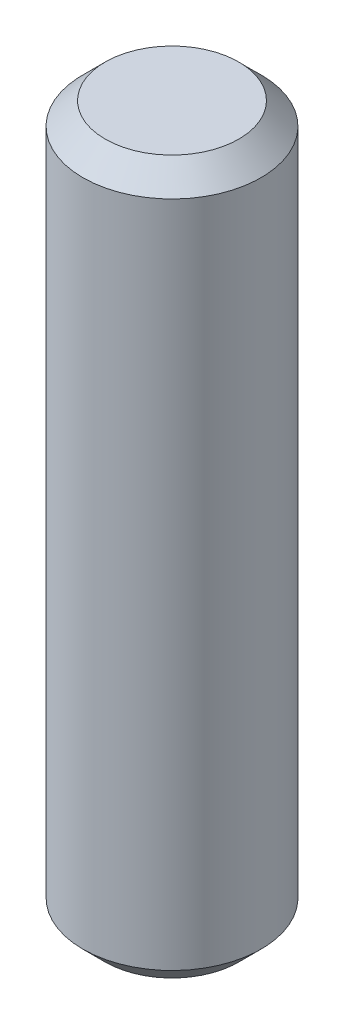
SolidWorks part; units mm, degrees
ref_plane "Front Plane" through (0, 0, 0) normal (0, 0, 1) x (1, 0, 0)
ref_plane "Top Plane" through (0, 0, 0) normal (0, 1, 0) x (1, 0, 0)
ref_plane "Right Plane" through (0, 0, 0) normal (1, 0, 0) x (0, 0, -1)
sketch "Sketch1" plane through (0, 0, 0) normal (0, 1, 0) x (1, 0, 0)
  circle A0 centre (0, 0) radius 1.5875
  dimension "D1" = 3.175
extrude "Boss-Extrude1" add sketch "Sketch1" along normal blind 12.7
chamfer "Chamfer1" distance 0.3969 angle 45 2 edges at (0, 0, 1.5875) (0, 12.7, 1.5875)
